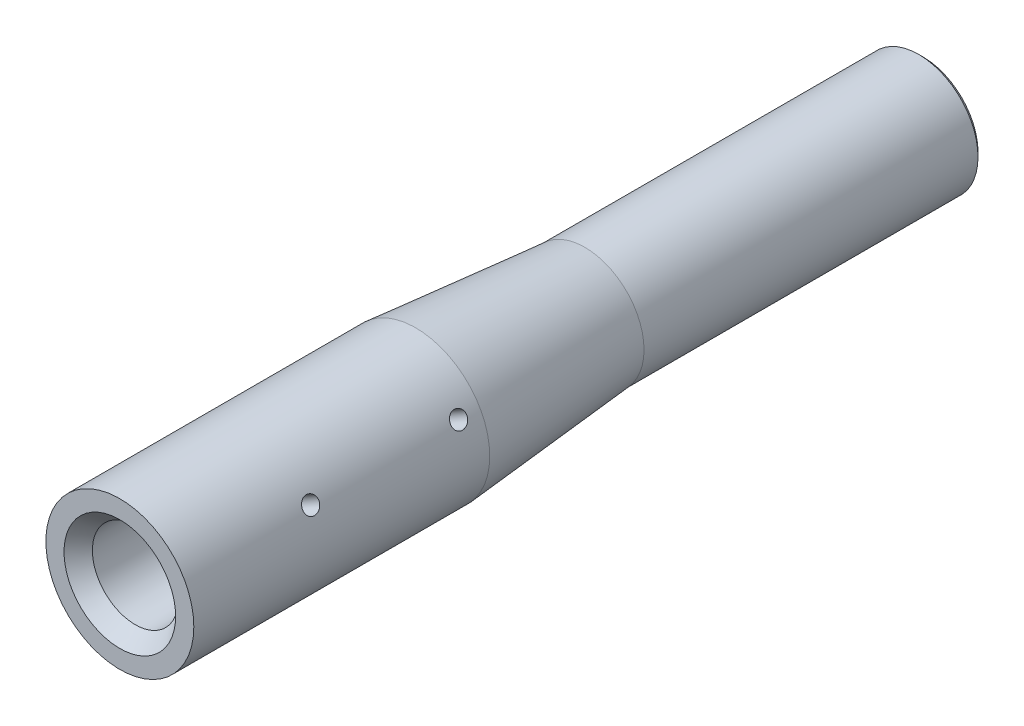
SolidWorks part; units mm, degrees
ref_plane "정면" through (0, 0, 0) normal (0, 0, 1) x (1, 0, 0)
ref_plane "윗면" through (0, 0, 0) normal (0, 1, 0) x (1, 0, 0)
ref_plane "우측면" through (0, 0, 0) normal (1, 0, 0) x (0, 0, -1)
sketch "스케치2" plane through (0, 0, 0) normal (1, 0, 0) x (0, 0, -1)
  line L0 (0, -10.2) -> (0, -17.5)
  line L1 (0, -17.5) -> (70, -17.5)
  line L2 (70, -17.5) -> (110, -14)
  line L3 (110, -14) -> (190, -14)
  line L4 (190, -14) -> (190, 0)
  line L5 (0, 0) -> (210, 0) construction
  line L6 (0, 0) -> (190, 0)
  line L7 (0.9197, -10.1853) -> (72, -9.05)
  line L8 (72, -9.05) -> (79.5, -7.175)
  line L9 (79.5, -7.175) -> (95.5, -7.175)
  line L10 (95.5, -7.175) -> (95.5, 0)
  line L11 (95.5, 0) -> (-4, 0)
  line L12 (-4, 0) -> (-4, -10.2)
  line L13 (-4, -10.2) -> (-2, -10.2)
  line L14 (-2, -10.2) -> (-2, -8.55)
  line L15 (-2, -8.55) -> (0.9197, -8.55)
  line L16 (0.9197, -8.55) -> (0.9197, -10.1853)
  line L17 (0, 0) -> (0, -10.2) construction
  line L18 (-2, -10.2) -> (0, -10.2) construction
  line L19 (0, -10.2) -> (0.9197, -10.1853)
  dimension "D1" = 190
  dimension "D2" = 35
  dimension "D3" = 28
  dimension "D4" = 70
  dimension "D5" = 40
  dimension "D6" = 210
  dimension "D7" = 10.2
  dimension "D8" = 2
  dimension "D9" = 2.9197
  dimension "D10" = 8.55
  dimension "D11" = 99.5
  dimension "D12" = 18.1
  dimension "D13" = 14.35
  dimension "D14" = 7.5
  dimension "D15" = 16
  dimension "D16" = 4
revolve "회전1" add sketch "스케치2" angle 360 about L5
ref_plane "평면1" through (0, -17.5, 0) normal (0, -1, 0) x (-1, 0, 0)
sketch "스케치5" plane through (0, -17.5, 0) normal (0, -1, 0) x (-1, 0, 0)
  line L0 (0, 65) -> (0, 30) construction
  line L1 (0, 30) -> (0, 0) construction
  circle A0 centre (0, 30) radius 1.925
  circle A1 centre (0, 65) radius 1.925
  dimension "D1" = 3.85
  dimension "D2" = 3.85
  dimension "D3" = 35
  dimension "D4" = 30
extrude "컷-돌출3" cut sketch "스케치5" against normal blind 6.5
pattern_circular "원형 패턴1" count 3 over 360 about axis through (0, 0, 0) along (0, 0, 1) of "컷-돌출3"
sketch "스케치6" plane through (0, 0, -95.5) normal (0, 0, 1) x (1, 0, 0)
  circle A0 centre (0, 0) radius 10.15
  dimension "D1" = 20.3
extrude "컷-돌출4" cut sketch "스케치6" against normal up to next
chamfer "모따기1" distance 1 angle 45 1 edges at (14, 0, -190)
chamfer "모따기2" distance 0.5 angle 45 1 edges at (-10.15, 0, -190)
chamfer "모따기3" distance 3 angle 50 1 edges at (10.2, 0, 0)
